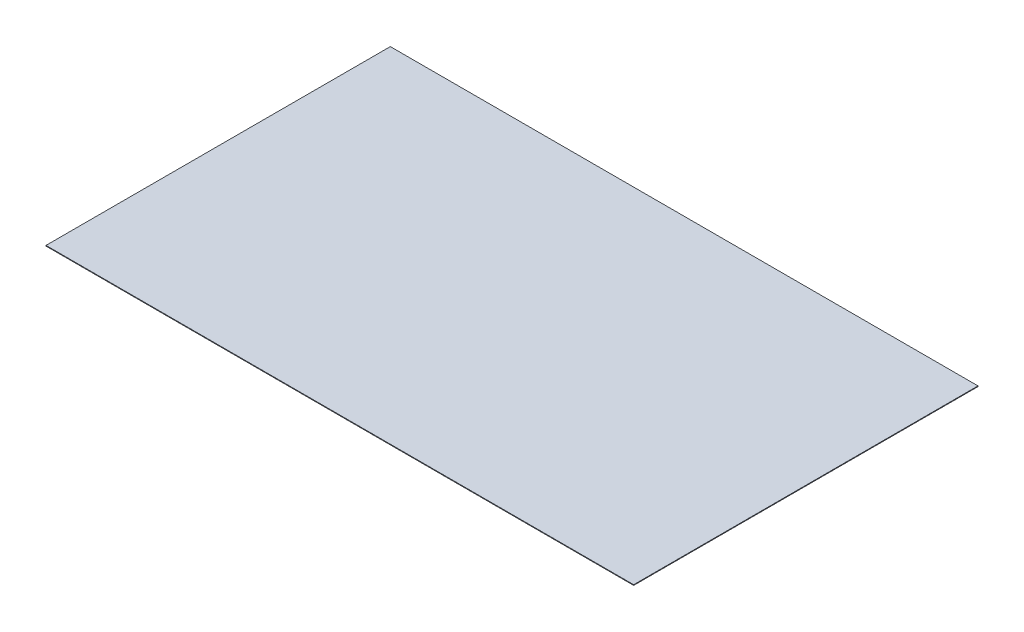
SolidWorks part; units mm, degrees
ref_plane "Front Plane" through (0, 0, 0) normal (0, 0, 1) x (1, 0, 0)
ref_plane "Top Plane" through (0, 0, 0) normal (0, 1, 0) x (1, 0, 0)
ref_plane "Right Plane" through (0, 0, 0) normal (1, 0, 0) x (0, 0, -1)
other "Configuration Table"
sketch "Sketch1" plane through (0, 0, 0) normal (0, 0, 1) x (1, 0, 0)
  line L1 (1.5, 120) -> (1398.5, 120)
  line L2 (1.5, 120) -> (1.5, 121.5)
  line L3 (1.5, 121.5) -> (1398.5, 121.5)
  line L4 (1398.5, 120) -> (1398.5, 121.5)
extrude "STORE_dis_alt_1" add sketch "Sketch1" against normal blind 818.5 separate body
